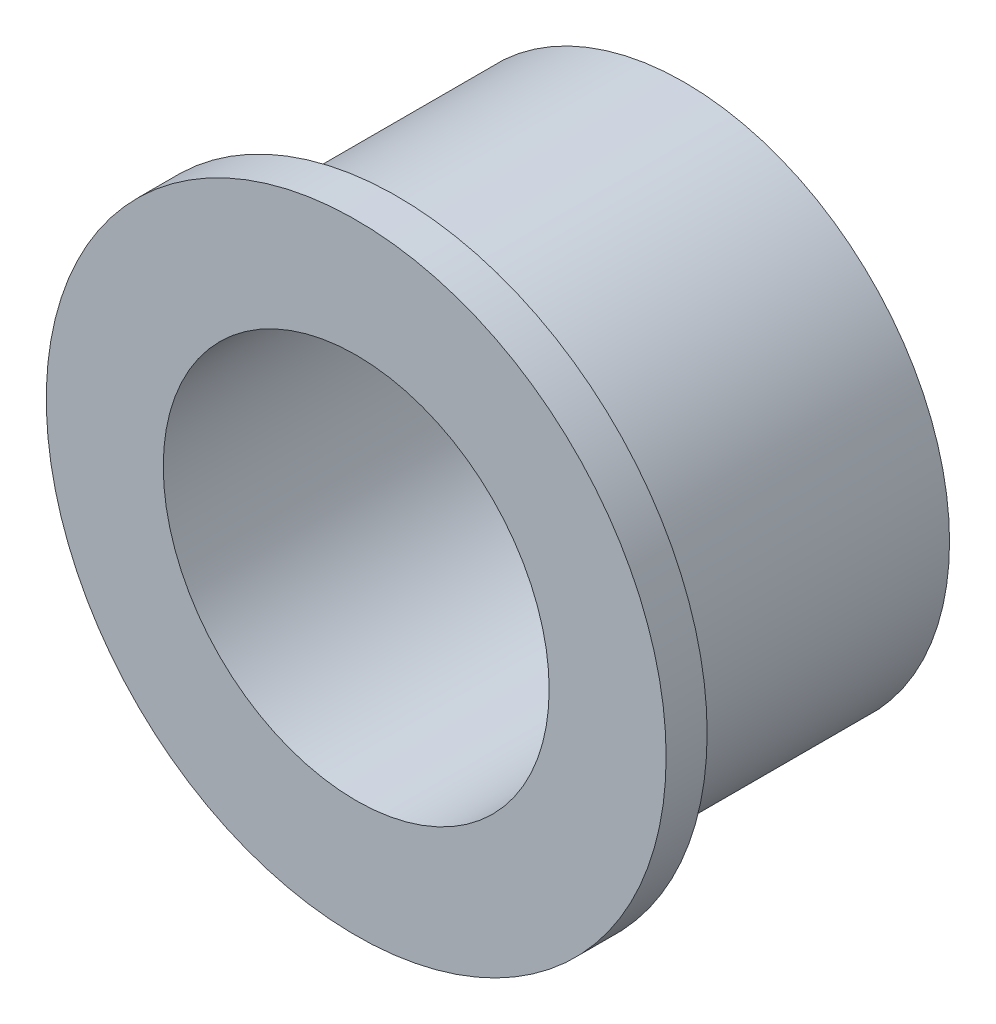
SolidWorks part; units mm, degrees
ref_plane "Front Plane" through (0, 0, 0) normal (0, 0, 1) x (1, 0, 0)
ref_plane "Top Plane" through (0, 0, 0) normal (0, 1, 0) x (1, 0, 0)
ref_plane "Right Plane" through (0, 0, 0) normal (1, 0, 0) x (0, 0, -1)
sketch "Sketch1" plane through (0, 0, 0) normal (1, 0, 0) x (0, 0, -1)
  line L0 (0, 0) -> (10.9945, 0) construction
  line L1 (0, 2.032) -> (0, 3.2639)
  line L2 (0, 3.2639) -> (0.4318, 3.2639)
  line L3 (0.4318, 3.2639) -> (0.4318, 2.794)
  line L4 (0.4318, 2.794) -> (3.4544, 2.794)
  line L5 (3.4544, 2.794) -> (3.4544, 2.032)
  line L6 (3.4544, 2.032) -> (0, 2.032)
  dimension "D1" = 2.032
  dimension "D2" = 3.2639
  dimension "D3" = 2.794
  dimension "D4" = 3.4544
  dimension "D5" = 0.4318
revolve "Revolve1" add sketch "Sketch1" angle 360 about L0
scale "Scale1" scale about centroid uniform scaling yes scale factor 0.6
